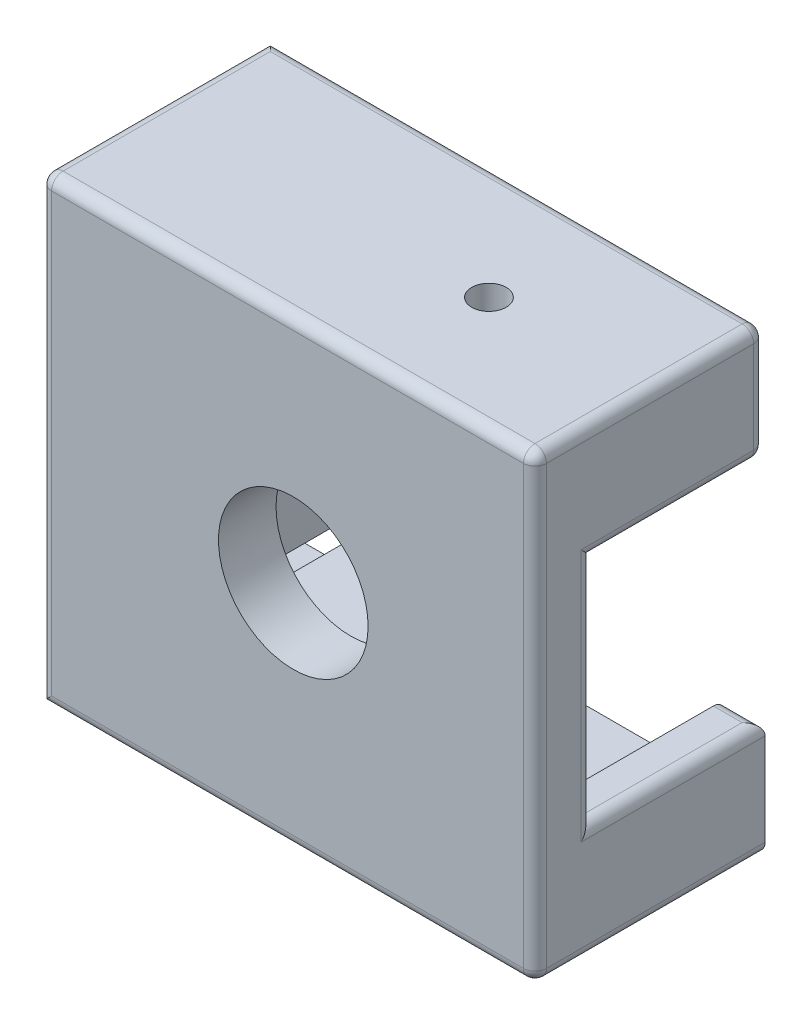
SolidWorks part; units mm, degrees
ref_plane "Front Plane" through (0, 0, 0) normal (0, 0, 1) x (1, 0, 0)
ref_plane "Top Plane" through (0, 0, 0) normal (0, 1, 0) x (1, 0, 0)
ref_plane "Right Plane" through (0, 0, 0) normal (1, 0, 0) x (0, 0, -1)
sketch "Sketch1" plane through (0, 0, 0) normal (0, 0, 1) x (1, 0, 0)
  line L0 (92.0048, 6.2146) -> (46.0048, 6.2146) construction
  line L1 (97.0048, 11.2146) -> (54.0048, 11.2146)
  line L2 (97.0048, 11.2146) -> (97.0048, -28.7854)
  line L3 (97.0048, -28.7854) -> (54.0048, -28.7854)
  line L4 (54.0048, 11.2146) -> (54.0048, -28.7854)
  line L5 (92.0048, 6.2146) -> (92.0048, -0.2854) construction
  dimension "D1" = 40
  dimension "D2" = 43
  dimension "D3" = 5
  dimension "D4" = 5
extrude "Boss-Extrude1" add sketch "Sketch1" along normal blind 5
sketch "Sketch2" plane through (0, 0, 0) normal (0, 0, -1) x (-1, 0, 0)
  line L0 (-97.0048, -28.7854) -> (-97.0048, 11.2146) construction
  line L5 (-72.5048, 0.5146) -> (-85.5048, 0.5146)
  line L6 (-72.5048, 0.5146) -> (-72.5048, -1.4854)
  line L7 (-72.5048, -1.4854) -> (-85.5048, -1.4854)
  line L8 (-85.5048, 0.5146) -> (-85.5048, -1.4854)
  line L13 (-68.0048, -15.9854) -> (-85.5048, -15.9854)
  line L15 (-68.0048, -17.9854) -> (-85.5048, -17.9854)
  line L16 (-85.5048, -15.9854) -> (-85.5048, -17.9854)
  line L17 (-54.0048, -28.7854) -> (-97.0048, -28.7854) construction
  line L18 (-97.0048, 11.2146) -> (-54.0048, 11.2146) construction
  line L19 (-68.0048, -15.9854) -> (-68.0048, -17.9854)
  line L25 (-68.0048, -4.2854) -> (-65.5048, -4.2854)
  line L26 (-68.0048, -4.2854) -> (-68.0048, -14.2854)
  line L27 (-68.0048, -14.2854) -> (-65.5048, -14.2854)
  line L28 (-65.5048, -4.2854) -> (-65.5048, -14.2854)
  point P18 (-66.7548, -14.2854)
  dimension "D1" = 2
  dimension "D2" = 13
  dimension "D3" = 11.5
  dimension "D4" = 10
  dimension "D5" = 2.5
  dimension "D6" = 2
  dimension "D7" = 17.5
  dimension "D8" = 14.5
  dimension "D9" = 10.8
  dimension "D10" = 11.5
  dimension "D11" = 29
  dimension "D12" = 10.7
extrude "Boss-Extrude3" add sketch "Sketch2" along normal blind 8 contours L26 L27 L28 L25 | L19 L15 L16 L13 | L6 L5 L8 L7
sketch "Sketch3" plane through (0, 0, 0) normal (0, 0, -1) x (-1, 0, 0)
  line L0 (-54.0048, 11.2146) -> (-97.0048, 11.2146)
  line L1 (-97.0048, 11.2146) -> (-97.0048, -28.7854)
  line L2 (-97.0048, -28.7854) -> (-54.0048, -28.7854)
  line L3 (-54.0048, -28.7854) -> (-54.0048, -25.2854)
  line L4 (-54.0048, 11.2146) -> (-54.0048, -28.7854) construction
  line L5 (-54.0048, -25.2854) -> (-93.5048, -25.2854)
  line L6 (-93.5048, -25.2854) -> (-93.5048, 7.7146)
  line L7 (-93.5048, 7.7146) -> (-54.0048, 7.7146)
  line L8 (-54.0048, 7.7146) -> (-54.0048, 11.2146)
  dimension "D1" = 3.5
  dimension "D2" = 3.5
  dimension "D3" = 3.5
extrude "Boss-Extrude4" add sketch "Sketch3" along normal blind 15
sketch "Sketch4" plane through (0, 11.2146, 0) normal (0, 1, 0) x (1, 0, 0)
  line L0 (97.0048, -5) -> (97.0048, 15) construction
  line L1 (97.0048, -5) -> (54.0048, -5) construction
  circle A0 centre (83.0048, 5) radius 1.5
  dimension "D1" = 14
  dimension "D2" = 10
  dimension "D3" = 3
extrude "Cut-Extrude1" cut sketch "Sketch4" against normal blind 65
sketch "Sketch6" plane through (0, -28.7854, 0) normal (0, -1, 0) x (1, 0, 0)
  line L0 (54.0048, 5) -> (54.0048, -15) construction
  circle A0 centre (60.0048, -5) radius 1.5
  circle A1 centre (83.0048, -5) radius 1.5 construction
  dimension "D1" = 0
  dimension "D2" = 6
  dimension "D3" = 3
extrude "Cut-Extrude2" cut sketch "Sketch6" against normal blind 10
sketch "Sketch7" plane through (0, 0, 5) normal (0, 0, 1) x (1, 0, 0)
  line L0 (54.0048, 11.2146) -> (54.0048, -28.7854) construction
  line L1 (97.0048, 11.2146) -> (54.0048, 11.2146) construction
  circle A0 centre (76.0048, -8.7854) radius 6.5
  dimension "D1" = 13
  dimension "D2" = 22
  dimension "D3" = 20
extrude "Cut-Extrude3" cut sketch "Sketch7" against normal blind 20
sketch "Sketch8" plane through (97.0048, 0, 0) normal (1, 0, 0) x (0, 0, -1)
  line L0 (15, 11.2146) -> (15, -28.7854) construction
  line L1 (15, 1.2146) -> (0, 1.2146)
  line L2 (15, 1.2146) -> (15, -18.7854)
  line L3 (15, -18.7854) -> (0, -18.7854)
  line L4 (0, 1.2146) -> (0, -18.7854)
  line L5 (-5, -28.7854) -> (-5, 11.2146) construction
  point P8 (-5, -8.7854)
  dimension "D1" = 20
  dimension "D2" = 10
  dimension "D3" = 15
extrude "Cut-Extrude4" cut sketch "Sketch8" against normal blind 5
fillet "Fillet1" radius 1 9 edges at (54.0048, 11.2146, -5) (54.0048, -8.7854, 5) (75.5048, -28.7854, 5) (97.0048, -28.7854, -5) (97.0048, -8.7854, 5) (75.5048, 11.2146, 5) (97.0048, 11.2146, -5) (97.0048, 6.2146, -15) (75.5048, 11.2146, -15)
fillet "Fillet2" radius 1 6 edges at (96.7119, 1.2146, -14.7071) (94.7548, 1.2146, -15) (95.2548, -18.7854, -15) (97.0048, -8.7854, 0) (97.0048, 1.2146, -7) (97.0048, -18.7854, -7.5)
